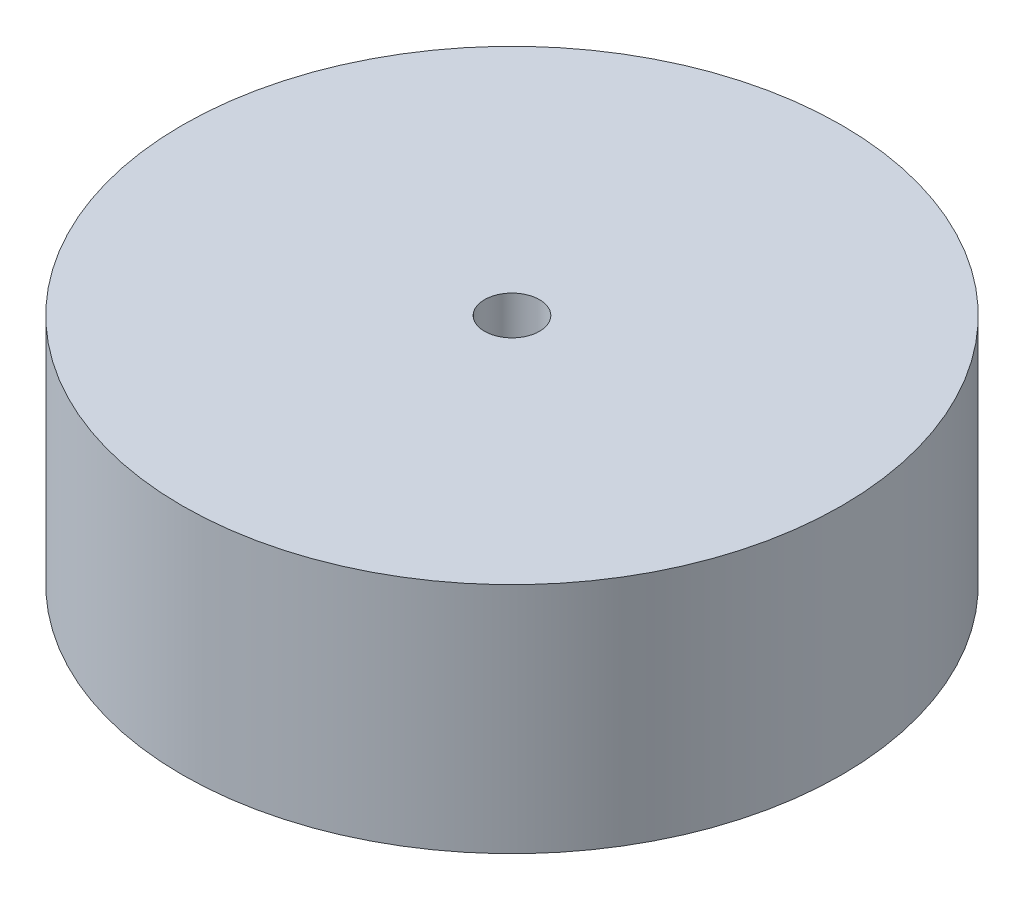
SolidWorks part; units mm, degrees
ref_plane "Front Plane" through (0, 0, 0) normal (0, 0, 1) x (1, 0, 0)
ref_plane "Top Plane" through (0, 0, 0) normal (0, 1, 0) x (1, 0, 0)
ref_plane "Right Plane" through (0, 0, 0) normal (1, 0, 0) x (0, 0, -1)
sketch "Sketch3" plane through (0, 0, 0) normal (0, 1, 0) x (1, 0, 0)
  line L0 (0, 0) -> (0, 38.1) construction
  circle A0 centre (0, 0) radius 38.1
  dimension "D1" = 76.2
extrude "Boss-Extrude1" add sketch "Sketch3" along normal blind 26.924
hole_wizard "1/4 (0.2500) Dowel Hole2" positions "Sketch6" profile "Sketch7" hole size "1/4" standard "ANSI Inch" end condition through all
sketch "Sketch6" plane through (0, 26.924, 0) normal (0, 1, 0) x (1, 0, 0)
  point P0 (0, 0)
sketch "Sketch7" plane through (0, 26.924, 0) normal (1, 0, 0) x (0, 0, 1)
  line L0 (0, 0) -> (0, 26.924)
  line L1 (0, 26.924) -> (3.175, 26.924)
  line L2 (3.175, 26.924) -> (3.175, 0)
  line L5 (3.175, 0) -> (0, 0)
  line L11 (0, -6.35) -> (0, 107.95) construction
  dimension "Thru Hole Dia." = 6.35
  dimension "Thru Hole Depth" = 26.924
sketch "Sketch8" plane through (0, 26.924, 0) normal (0, 1, 0) x (1, 0, 0)
  line L0 (0, -3.175) -> (0, -38.1) construction
  circle A0 centre (0, 0) radius 3.175 construction
  circle A1 centre (0, 0) radius 38.1 construction
